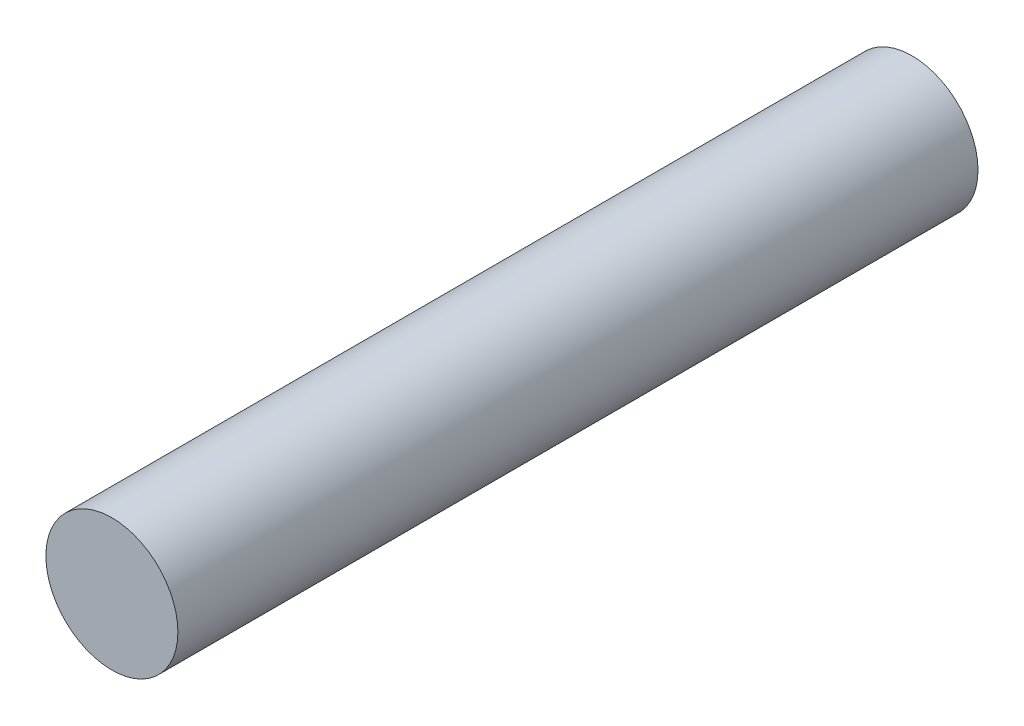
SolidWorks part; units mm, degrees
ref_plane "Front Plane" through (0, 0, 0) normal (1, 0, 0) x (0, 1, 0)
ref_plane "Top Plane" through (0, 0, 0) normal (0, 0, 1) x (0, 1, 0)
ref_plane "Right Plane" through (0, 0, 0) normal (0, 1, 0) x (-1, 0, 0)
sketch "Sketch1" plane through (0, 0, 0) normal (0, 0, 1) x (0, 1, 0)
  circle A0 centre (0, 0) radius 16.5
  dimension "D1" = 33
extrude "Boss-Extrude1" add sketch "Sketch1" along normal blind 200
